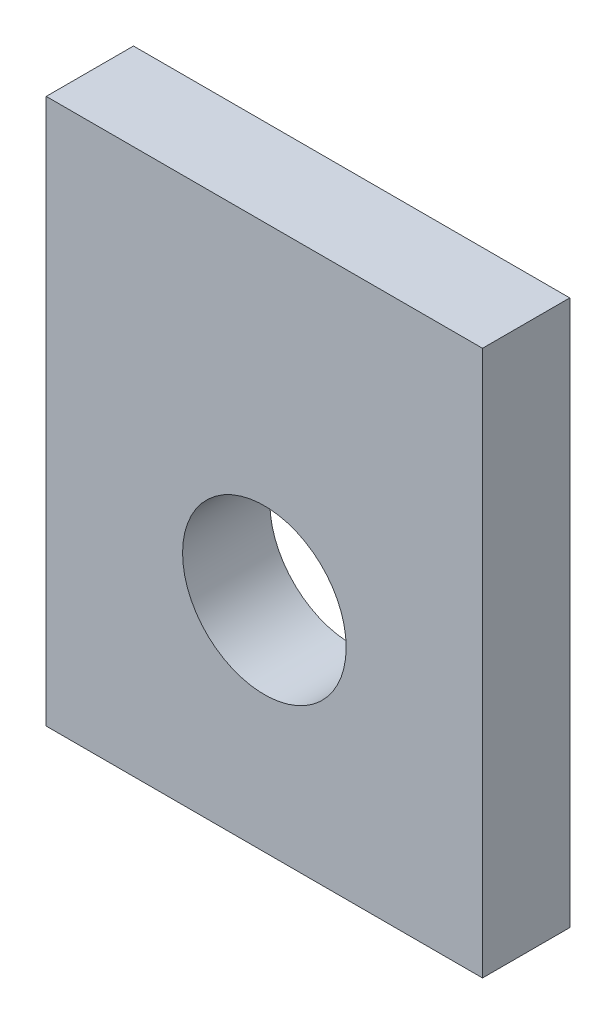
SolidWorks part; units mm, degrees
material "ASTM A36 Steel"
ref_plane "Front Plane" through (0, 0, 0) normal (0, 0, 1) x (1, 0, 0)
ref_plane "Top Plane" through (0, 0, 0) normal (0, 1, 0) x (1, 0, 0)
ref_plane "Right Plane" through (0, 0, 0) normal (1, 0, 0) x (0, 0, -1)
sketch "Sketch1" plane through (0, 0, 0) normal (0, 0, 1) x (1, 0, 0)
  line L1 (26.7273, 21.9091) -> (-13.2727, 21.9091)
  line L2 (26.7273, 21.9091) -> (26.7273, -28.0909)
  line L3 (26.7273, -28.0909) -> (-13.2727, -28.0909)
  line L4 (-13.2727, 21.9091) -> (-13.2727, -28.0909)
  circle A0 centre (6.7273, -8.0909) radius 7.5
  dimension "D4" = 15
  dimension "D5" = 20
  dimension "D1" = 50
  dimension "D2" = 40
  dimension "D3" = 20
extrude "Boss-Extrude1" add sketch "Sketch1" along normal blind 8
